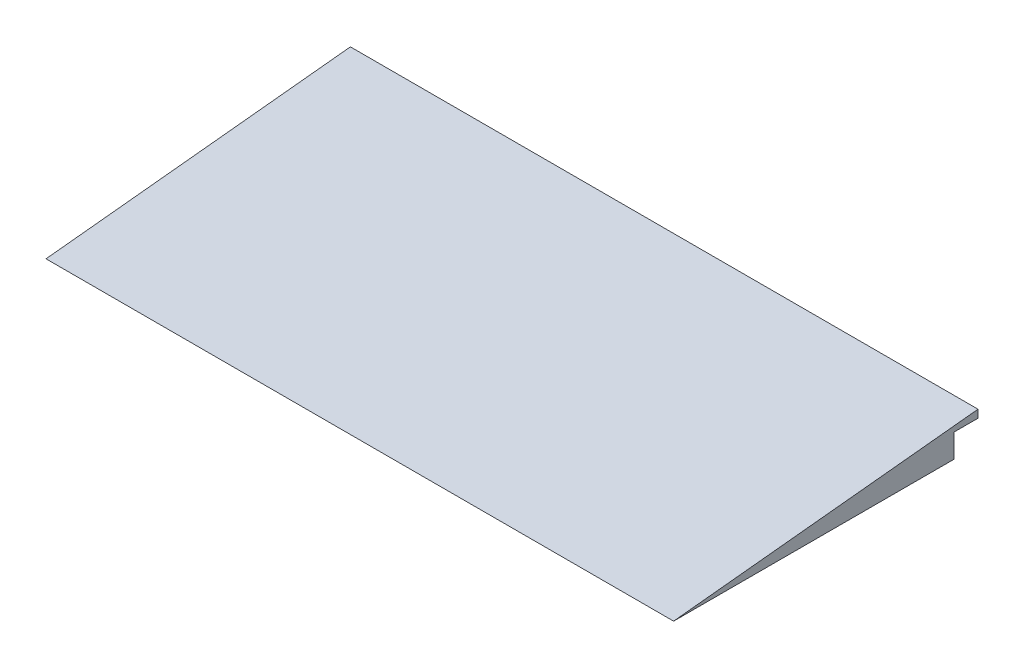
SolidWorks part; units mm, degrees
ref_plane "Front Plane" through (0, 0, 0) normal (0, 0, 1) x (1, 0, 0)
ref_plane "Top Plane" through (0, 0, 0) normal (0, 1, 0) x (1, 0, 0)
ref_plane "Right Plane" through (0, 0, 0) normal (1, 0, 0) x (0, 0, -1)
sketch "Sketch1" plane through (0, 0, 0) normal (1, 0, 0) x (0, 0, -1)
  line L0 (-48.5, 0) -> (48.5, 10)
  line L1 (48.5, 0) -> (-48.5, 0)
  line L5 (0, 55) -> (0, -55) construction
  line L6 (55, 0) -> (-55, 0) construction
  line L7 (48.5, 10) -> (48.5, 0)
  point P0 (0, 0)
  point P3 (0, 0)
  dimension "D2" = 10
  dimension "D3" = 97
extrude "Boss-Extrude1" add sketch "Sketch1" along normal mid plane 200
sketch "Sketch3" plane through (100, 0, 0) normal (1, 0, 0) x (0, 0, -1)
  line L0 (55, 0) -> (-55, 0) construction
  line L1 (48.5, 0) -> (40.8, 0)
  line L2 (48.5, 0) -> (48.5, 7.5)
  line L3 (48.5, 7.5) -> (40.8, 7.5)
  line L4 (40.8, 0) -> (40.8, 7.5)
  line L5 (48.5, 0) -> (48.5, 10) construction
  dimension "D1" = 7.7
  dimension "D2" = 7.5
extrude "Cut-Extrude1" cut sketch "Sketch3" against normal through all
